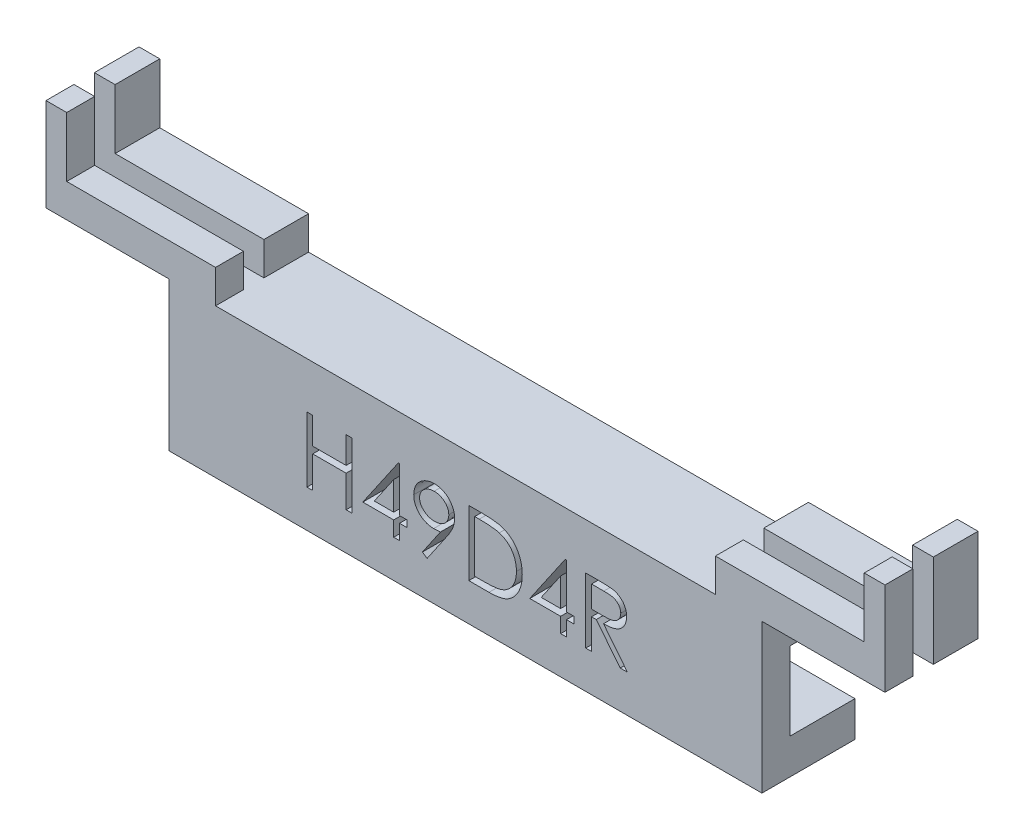
SolidWorks part; units mm, degrees
ref_plane "Front Plane" through (0, 0, 0) normal (0, 0, 1) x (1, 0, 0)
ref_plane "Top Plane" through (0, 0, 0) normal (0, 1, 0) x (1, 0, 0)
ref_plane "Right Plane" through (0, 0, 0) normal (1, 0, 0) x (0, 0, -1)
sketch "Sketch2" plane through (0, 0, 0) normal (0, 0, 1) x (1, 0, 0)
  line L0 (21.4353, 2.5) -> (21.4353, -0.7101)
  line L1 (-22.55, 2.5) -> (-21.4353, 2.5)
  line L2 (-22.55, 2.5) -> (-22.55, -2.5)
  line L3 (-22.55, -2.5) -> (-13.4354, -2.5)
  line L4 (22.55, 2.5) -> (22.55, -2.5)
  line L5 (-22.55, 2.5) -> (-21.4353, 2.3764) construction
  line L6 (-22.55, -2.5) -> (-13.4354, -1.4895) construction
  line L7 (21.4353, -0.7101) -> (13.4354, -0.7101)
  line L8 (13.4354, -0.7101) -> (13.4354, -2.5)
  line L9 (0, 0) -> (0, 5.8213) construction
  line L10 (-21.4353, 2.5) -> (-21.4353, -0.7101)
  line L11 (-21.4353, -0.7101) -> (-13.4354, -0.7101)
  line L12 (-13.4354, -0.7101) -> (-13.4354, -2.5)
  line L13 (21.4353, 2.5) -> (22.55, 2.5)
  line L14 (13.4354, -1.4895) -> (22.55, -2.5) construction
  line L15 (21.4353, 2.3764) -> (22.55, 2.5) construction
  line L16 (13.4354, -2.5) -> (22.55, -2.5)
  point P0 (0, 0)
  dimension "D1" = 45.1
  dimension "D2" = 5
extrude "Boss-Extrude1" add sketch "Sketch2" against normal blind 5
sketch "Sketch4" plane through (0, 0, 0) normal (0, 0, 1) x (1, 0, 0)
  line L0 (-13.4354, -2.5) -> (-15.9354, -2.5) construction
  line L1 (-22.55, -2.5) -> (-13.4354, -2.5) construction
  line L2 (13.4354, -2.5) -> (15.9354, -2.5) construction
  line L3 (13.4354, -2.5) -> (22.55, -2.5) construction
  line L5 (-15.9354, -2.5) -> (15.9354, -2.5)
  line L6 (-15.9354, -2.5) -> (-15.9354, -10.5)
  line L7 (-15.9354, -10.5) -> (15.9354, -10.5)
  line L8 (15.9354, -2.5) -> (15.9354, -10.5)
  dimension "D1" = 2.5
  dimension "D2" = 2.5
  dimension "D3" = 8
extrude "Boss-Extrude2" add sketch "Sketch4" against normal blind 5
sketch "Sketch5" plane through (0, 0, -5) normal (0, 0, -1) x (-1, 0, 0)
  line L0 (0, -10.5) -> (0, -1.4976) construction
  line L1 (15.9354, -10.5) -> (-15.9354, -10.5) construction
  line L3 (-16.3381, -4.4) -> (16.3381, -4.4)
  line L4 (-16.3381, -4.4) -> (-16.3381, -8.6)
  line L5 (-16.3381, -8.6) -> (16.3381, -8.6)
  line L6 (16.3381, -4.4) -> (16.3381, -8.6)
  line L7 (-16.3381, -4.4) -> (16.3381, -8.6) construction
  line L8 (-16.3381, -8.6) -> (16.3381, -4.4) construction
  point P5 (0, -6.5)
  dimension "D1" = 4.2
extrude "Cut-Extrude1" cut sketch "Sketch5" against normal blind 3.5
sketch "Sketch6" plane through (0, 2.5, 0) normal (0, 1, 0) x (1, 0, 0)
  line L0 (22.55, 5) -> (22.55, 0) construction
  line L1 (-22.55, 1.5) -> (22.55, 1.5)
  line L2 (-22.55, 1.5) -> (-22.55, 2.6)
  line L3 (-22.55, 2.6) -> (22.55, 2.6)
  line L4 (22.55, 1.5) -> (22.55, 2.6)
  line L5 (-22.55, 1.5) -> (22.55, 2.6) construction
  line L6 (-22.55, 2.6) -> (22.55, 1.5) construction
  line L7 (13.4354, 0) -> (-13.4354, 0) construction
  point P0 (0, 2.05)
  dimension "D1" = 1.5
  dimension "D2" = 1.1
extrude "Cut-Extrude2" cut sketch "Sketch6" against normal blind 5
sketch "Sketch10" plane through (0, 0, 0) normal (0, 0, 1) x (1, 0, 0)
  line L0 (-15.9354, -8.485) -> (15.9354, -8.485) construction
  line L1 (-15.9354, -2.5) -> (-15.9354, -10.5) construction
  line L2 (15.9354, -10.5) -> (15.9354, -2.5) construction
  text T0 "H49D4R"
extrude "Cut-Extrude4" cut sketch "Sketch10" against normal blind 10
